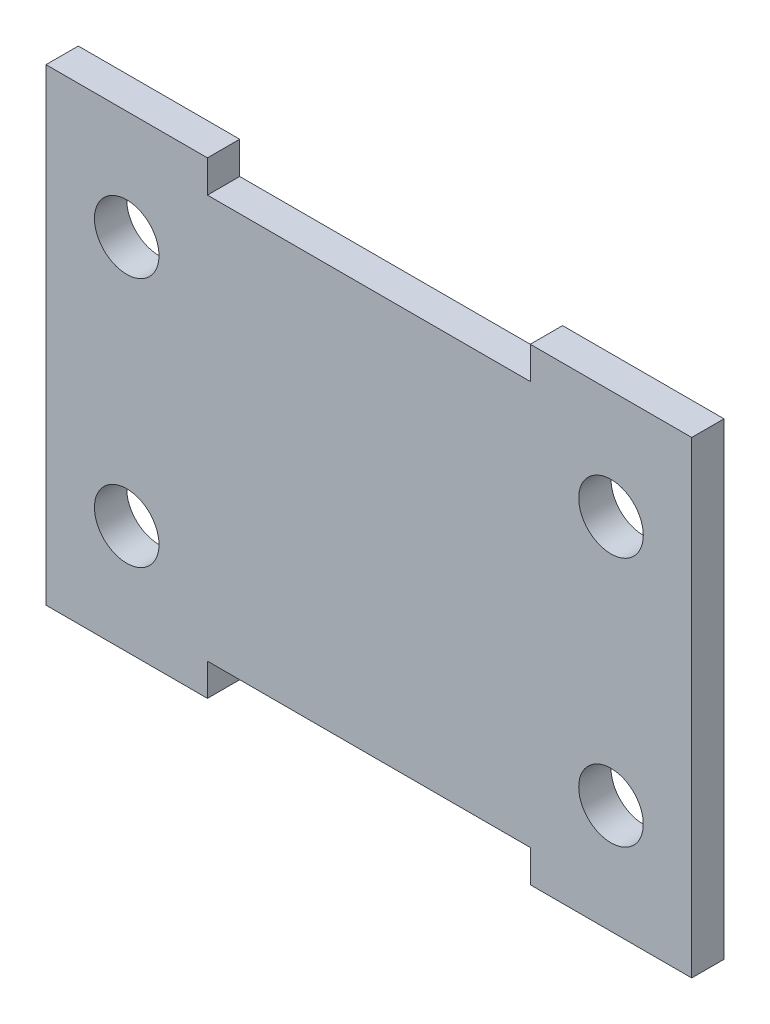
SolidWorks part; units mm, degrees
ref_plane "Front Plane" through (0, 0, 0) normal (0, 0, 1) x (1, 0, 0)
ref_plane "Top Plane" through (0, 0, 0) normal (0, 1, 0) x (1, 0, 0)
ref_plane "Right Plane" through (0, 0, 0) normal (1, 0, 0) x (0, 0, -1)
sketch "Sketch1" plane through (0, 0, 0) normal (0, 0, 1) x (1, 0, 0)
  line L0 (-40, 0) -> (64.7716, 0) construction
  line L1 (-20, 25) -> (20, 25)
  line L2 (-40, 25) -> (-40, -25)
  line L3 (-20, -25) -> (20, -25)
  line L4 (40, 25) -> (40, -25)
  line L5 (-40, 25) -> (40, -25) construction
  line L6 (-40, -25) -> (40, 25) construction
  line L7 (0, -10.0508) -> (0, 10.0508) construction
  line L8 (-40, 25) -> (40, -25) construction
  line L9 (-40, -25) -> (40, 25) construction
  line L10 (-20, -25) -> (-20, -29)
  line L12 (-40, 25) -> (-40, 29)
  line L13 (-40, 29) -> (-20, 29)
  line L14 (-20, 25) -> (-20, 29)
  line L15 (-40, -29) -> (-20, -29)
  line L16 (-40, -25) -> (-40, -29)
  line L19 (40, -25) -> (40, -29)
  line L20 (40, -29) -> (20, -29)
  line L21 (20, -25) -> (20, -29)
  line L22 (20, 25) -> (20, 29)
  line L23 (40, 29) -> (20, 29)
  line L24 (40, 25) -> (40, 29)
  circle A0 centre (30, 15.5) radius 4
  circle A1 centre (-30, 15.5) radius 4
  circle A2 centre (-30, -15.5) radius 4
  circle A3 centre (30, -15.5) radius 4
  point P0 (0, 0)
  point P15 (0, 0)
  point P31 (0, 0)
  dimension "D5" = 8
  dimension "D1" = 80
  dimension "D2" = 31
  dimension "D3" = 50
  dimension "D4" = 30
  dimension "D6" = 20
  dimension "D7" = 4
extrude "Boss-Extrude1" add sketch "Sketch1" along normal blind 4
